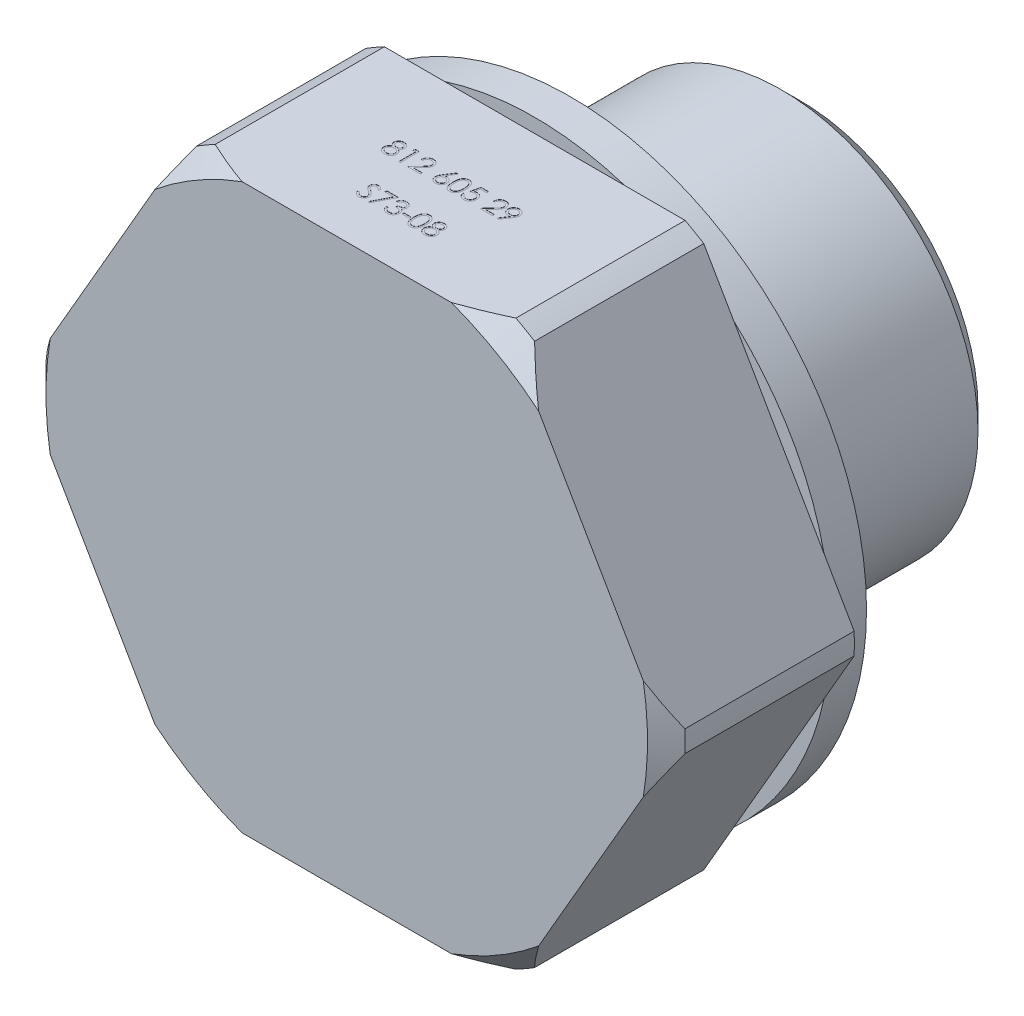
SolidWorks part; units mm, degrees
ref_plane "Front Plane" through (0, 0, 0) normal (0, 0, 1) x (1, 0, 0)
ref_plane "Top Plane" through (0, 0, 0) normal (0, 1, 0) x (1, 0, 0)
ref_plane "Right Plane" through (0, 0, 0) normal (1, 0, 0) x (0, 0, -1)
sketch "Sketch1" plane through (0, 0, 0) normal (1, 0, 0) x (0, 0, -1)
  line L0 (0, 0) -> (106.168, 0) construction
  line L1 (0, 0) -> (0, 16)
  line L2 (1, 17) -> (10, 17)
  line L3 (10, 17) -> (10, 9.48)
  line L4 (12, 10.48) -> (23.1, 10.48)
  line L5 (23.1, 10.48) -> (24.1, 9.48)
  line L6 (24.1, 9.48) -> (24.1, 0)
  line L7 (0, 0) -> (24.1, 0)
  line L8 (12, 10.48) -> (12, 9.48)
  line L9 (12, 9.48) -> (10, 9.48)
  line L10 (0, 16) -> (1, 17)
  point P4 (0, 17)
  dimension "D1" = 20.96
  dimension "D2" = 18.96
  dimension "D3" = 45
  dimension "D4" = 14.1
  dimension "D5" = 24.1
  dimension "D6" = 34
  dimension "D7" = 2
  dimension "D8" = 18.96
revolve "Revolve1" add sketch "Sketch1" angle 360 about L0
cosmetic thread "Cosmetic Thread1" parameters "D2"=18.6
sketch "Sketch2" plane through (0, 0, 0) normal (0, 0, 1) x (1, 0, 0)
  line L1 (-8.6603, 15) -> (-17.3205, 0)
  line L2 (-17.3205, 0) -> (-8.6603, -15)
  line L3 (-8.6603, -15) -> (8.6603, -15)
  line L4 (8.6603, -15) -> (17.3205, 0)
  line L5 (17.3205, 0) -> (8.6603, 15)
  line L6 (8.6603, 15) -> (-8.6603, 15)
  circle A0 centre (0, 0) radius 15 construction
  dimension "D1" = 30
extrude "Extrude1" cut sketch "Sketch2" against normal blind 10 flip side to cut
sketch "Sketch3" plane through (0, 0, 0) normal (1, 0, 0) x (0, 0, -1)
  line L0 (0, 0) -> (32.7239, 0) construction
  line L1 (10, 15.75) -> (11.9, 15.75)
  line L2 (10, 15.75) -> (10, 12.75)
  line L3 (10, 12.75) -> (11.9, 12.75)
  line L4 (11.9, 15.75) -> (11.9, 12.75)
  line L5 (10, -9.48) -> (10, 9.48) construction
  dimension "D1" = 1.9
  dimension "D2" = 31.5
  dimension "D3" = 25.5
revolve "Revolve2" add sketch "Sketch3" angle 360 about L0
sketch "Sketch4" plane through (0, 0, 0) normal (1, 0, 0) x (0, 0, -1)
  line L0 (0, 0) -> (29.8334, 0) construction
  line L1 (10, -12.75) -> (10, 12.75) construction
  circle A0 centre (11.2, 11.4) radius 1.2
  dimension "D1" = 2.4
  dimension "D2" = 22.8
  dimension "D3" = 1.2
revolve "Revolve3" add sketch "Sketch4" angle 360 about L0
sketch "Sketch5" plane through (0, 15, 0) normal (0, 1, 0) x (1, 0, 0)
  line L0 (-7.2087, 5.0951) -> (7.2475, 5.0951) construction
  text T0 "812 605 29\r\nS73-08" font "Century Gothic" height 1
extrude "Cut-Extrude1" cut sketch "Sketch5" against normal blind 0.01
